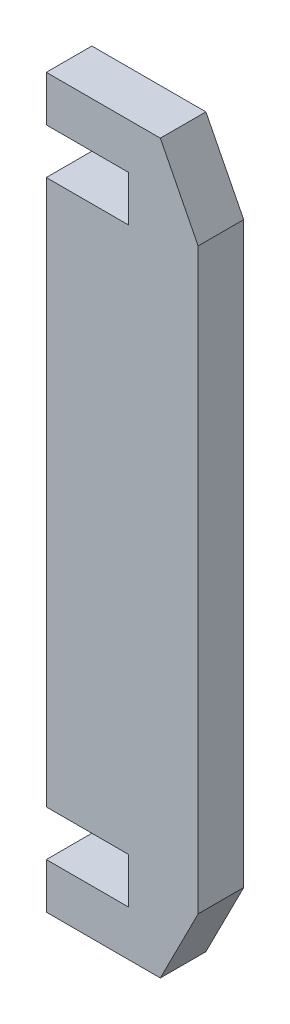
SolidWorks part; units mm, degrees
ref_plane "Front" through (0, 0, 0) normal (0, 0, 1) x (1, 0, 0)
ref_plane "Top" through (0, 0, 0) normal (0, 1, 0) x (1, 0, 0)
ref_plane "Right" through (0, 0, 0) normal (1, 0, 0) x (0, 0, -1)
sketch "Sketch1" plane through (0, 0, 0) normal (0, 0, 1) x (1, 0, 0)
  line L0 (882.9097, -114.5171) -> (882.9097, -76.4234)
  line L1 (878.3186, -74.5203) -> (878.3186, -77.5203)
  line L2 (878.3186, -113.4203) -> (878.3186, -116.4203)
  line L3 (880.4198, -119.4203) -> (882.9097, -114.5171)
  line L4 (872.9097, -116.4203) -> (872.9097, -119.4203)
  line L5 (872.9097, -119.4203) -> (880.4198, -119.4203)
  line L6 (872.9097, -77.5203) -> (872.9097, -103.4996)
  line L7 (878.3186, -116.4203) -> (872.9097, -116.4203)
  line L8 (872.9097, -71.5203) -> (872.9097, -74.5203)
  line L9 (878.3186, -74.5203) -> (872.9097, -74.5203)
  line L10 (872.9097, -71.5203) -> (880.4198, -71.5203)
  line L12 (880.4198, -71.5203) -> (882.9097, -76.4234)
  line L14 (872.9097, -77.5203) -> (878.3186, -77.5203)
  line L15 (872.9097, -113.4203) -> (872.9097, -103.4996)
  line L16 (872.9097, -113.4203) -> (878.3186, -113.4203)
  dimension "D1" = 3
  dimension "D2" = 3
  dimension "D3" = 3
  dimension "D4" = 35.9
  dimension "D5" = 3
  dimension "D6" = 10
extrude "Base-Extrude" add sketch "Sketch1" along normal blind 3
